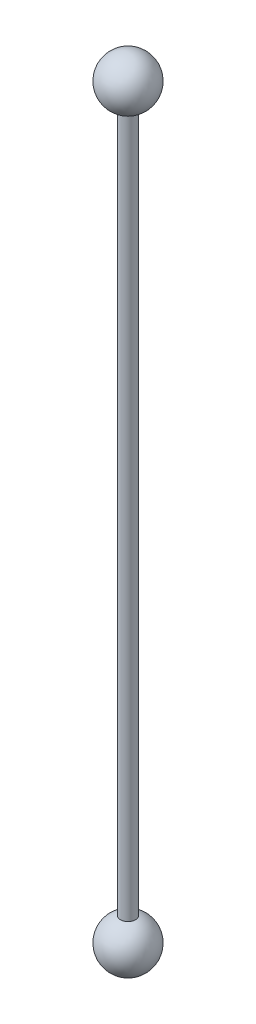
SolidWorks part; units mm, degrees
ref_plane "Front Plane" through (0, 0, 0) normal (0, 0, 1) x (1, 0, 0)
ref_plane "Top Plane" through (0, 0, 0) normal (0, 1, 0) x (1, 0, 0)
ref_plane "Right Plane" through (0, 0, 0) normal (1, 0, 0) x (0, 0, -1)
sketch "Sketch1" plane through (0, 0, 0) normal (0, 1, 0) x (1, 0, 0)
  circle A0 centre (0, 0) radius 1.5
extrude "Boss-Extrude1" add sketch "Sketch1" along normal blind 150
ref_plane "Plane1" through (0, 75, 0) normal (0, 1, 0) x (1, 0, 0)
sketch "Sketch2" plane through (0, 0, 0) normal (1, 0, 0) x (0, 0, -1)
  line L0 (0, 5) -> (0, -5)
  arc A0 (0, -5) -> (0, 5) centre (0, 0) ccw
revolve "Revolve1" add sketch "Sketch2" angle 360 about L0
mirror "Mirror1" about plane through (0, 75, 0) normal (0, 1, 0) of "Revolve1"
